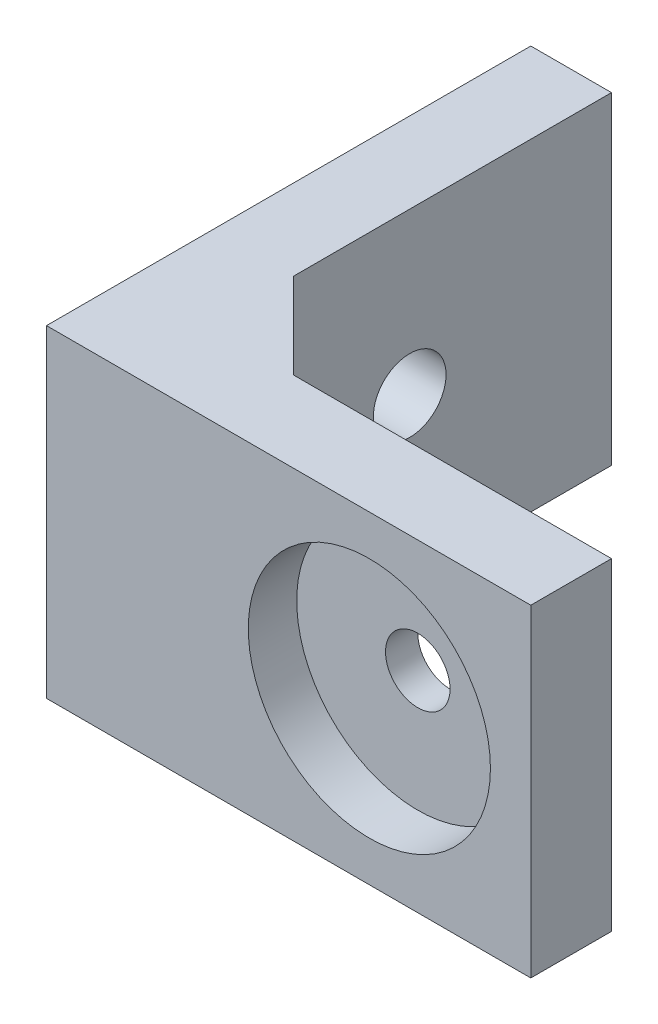
SolidWorks part; units mm, degrees
material "ABS"
ref_plane "Piano frontale" through (0, 0, 0) normal (0, 0, 1) x (1, 0, 0)
ref_plane "Piano superiore" through (0, 0, 0) normal (0, 1, 0) x (1, 0, 0)
ref_plane "Piano destro" through (0, 0, 0) normal (1, 0, 0) x (0, 0, -1)
sketch "Schizzo2" plane through (0, 0, 0) normal (0, 1, 0) x (1, 0, 0)
  line L0 (5, 30) -> (5, 10.3033)
  line L2 (10.3033, 5) -> (30, 5)
  line L3 (30, 5) -> (30, 0)
  line L4 (30, 0) -> (0, 0)
  line L5 (0, 0) -> (0, 30)
  line L6 (0, 30) -> (5, 30)
  line L7 (5, 10.3033) -> (10.3033, 5)
  dimension "D1" = 7.5
  dimension "D2" = 5
  dimension "D4" = 30
extrude "Estrusione-Estrusione2" add sketch "Schizzo2" along normal blind 20
sketch "Schizzo3" plane through (5, 0, 0) normal (1, 0, 0) x (0, 0, -1)
  line L0 (10.3033, 0) -> (30, 0) construction
  line L1 (30, 20) -> (30, 0) construction
  point P0 (17.5, 10)
  dimension "D1" = 10
  dimension "D2" = 12.5
hole_wizard "Foro per Vite M4-2" positions "Schizzo3" profile "Schizzo5" hole size "M4" standard "ISO"
sketch "Schizzo5" plane through (5, 10, -17.5) normal (0, 1, 0) x (0, 0, -1)
  line L0 (0, 0) -> (0, 16.3519)
  line L1 (0, 16.3519) -> (2.25, 15)
  line L2 (2.25, 15) -> (2.25, 0)
  line L5 (2.25, 0) -> (0, 0)
  line L10 (0, 16.3519) -> (-2.25, 15) construction
  line L11 (0, -6.35) -> (0, 107.95) construction
  dimension "Hole Dia." = 4.5
  dimension "Hole Depth" = 15
  dimension "Drill Angle" = 118
sketch "Schizzo6" plane through (0, 0, 0) normal (0, 0, 1) x (1, 0, 0)
  line L0 (0, 0) -> (30, 0) construction
  line L2 (30, 20) -> (30, 0) construction
  circle A0 centre (20, 10) radius 7.5
  dimension "D1" = 15
  dimension "D2" = 10
  dimension "D3" = 10
extrude "Taglio-Estrusione1" cut sketch "Schizzo6" against normal blind 3
hole_wizard "Foro per Vite M4-1" positions "Schizzo3D1" profile "Schizzo7" hole size "M4" standard "DIN"
sketch3d "Schizzo3D1"
  line L0 (20, 10, -3) -> (20, 10, 0) construction
  point P1 (20, 10, 0)
sketch "Schizzo7" plane through (20, 10, 0) normal (1, 0, 0) x (0, -1, 0)
  line L0 (0, 0) -> (0, 10.2017)
  line L1 (0, 10.2017) -> (2, 9)
  line L2 (2, 9) -> (2, 0)
  line L5 (2, 0) -> (0, 0)
  line L10 (0, 10.2017) -> (-2, 9) construction
  line L11 (0, -6.35) -> (0, 107.95) construction
  dimension "Hole Dia." = 4
  dimension "Hole Depth" = 9
  dimension "Drill Angle" = 118
